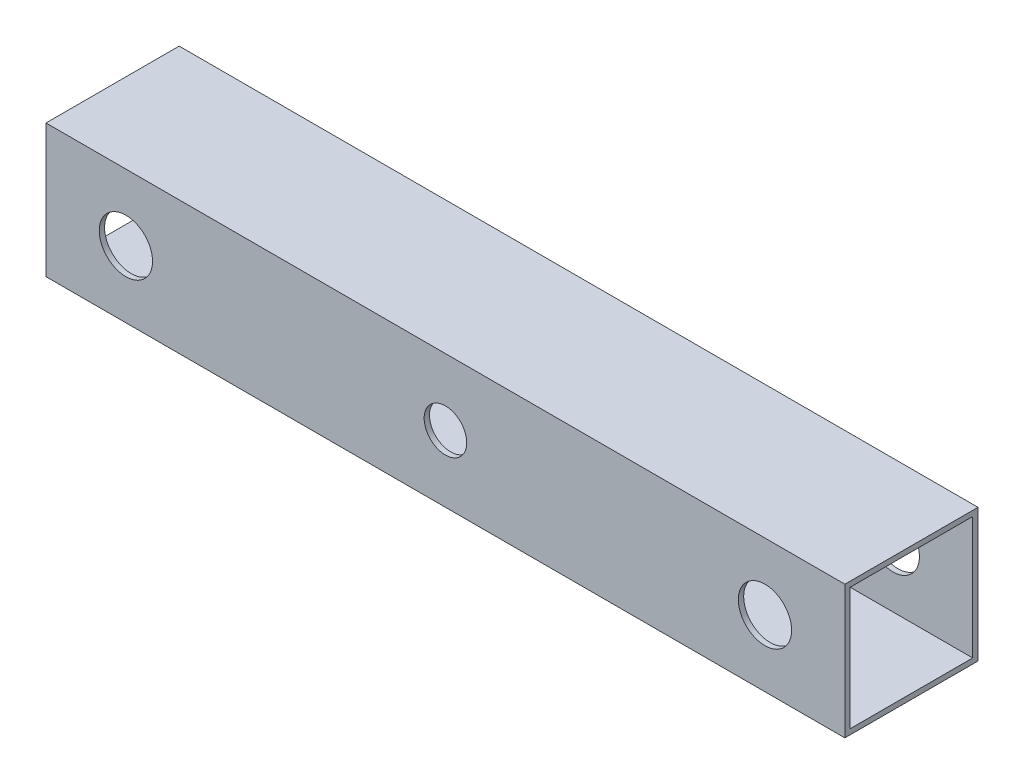
SolidWorks part; units mm, degrees
ref_plane "Front Plane" through (0, 0, 0) normal (0, 0, 1) x (1, 0, 0)
ref_plane "Top Plane" through (0, 0, 0) normal (0, 1, 0) x (1, 0, 0)
ref_plane "Right Plane" through (0, 0, 0) normal (1, 0, 0) x (0, 0, -1)
sketch "Sketch1" plane through (0, 0, 0) normal (1, 0, 0) x (0, 0, -1)
  line L0 (-12.5, 12.5) -> (12.5, 12.5)
  line L2 (-11.5, -11.5) -> (-11.5, 11.5)
  line L3 (-11.5, 11.5) -> (11.5, 11.5)
  line L5 (-11.5, -11.5) -> (11.5, 11.5) construction
  line L6 (-11.5, 11.5) -> (11.5, -11.5) construction
  line L7 (12.5, -12.5) -> (12.5, 12.5)
  line L8 (-12.5, -12.5) -> (12.5, -12.5)
  line L9 (-12.5, -12.5) -> (-12.5, 12.5)
  line L12 (-11.5, 11.5) -> (11.5, 11.5) construction
  line L13 (-11.5, -11.5) -> (11.5, -11.5)
  line L14 (-11.5, -11.5) -> (-11.5, 11.5) construction
  line L15 (11.5, -11.5) -> (11.5, 11.5)
  line L16 (-11.5, -11.5) -> (11.5, -11.5) construction
  line L18 (11.5, -11.5) -> (11.5, 11.5) construction
  point P0 (0, 0)
  dimension "D2" = 25
  dimension "D1" = 1
extrude "Boss-Extrude1" add sketch "Sketch1" along normal blind 150
sketch "Sketch2" plane through (0, 0, 12.5) normal (0, 0, 1) x (1, 0, 0)
  line L0 (0, 0) -> (150, 0) construction
  line L1 (150, 12.5) -> (150, -12.5) construction
  circle A0 centre (75, 0) radius 4
  circle A1 centre (15, 0) radius 5
  circle A2 centre (135, 0) radius 5
  dimension "D1" = 8
  dimension "D2" = 10
  dimension "D3" = 60
  dimension "D4" = 60
extrude "Cut-Extrude1" cut sketch "Sketch2" against normal through all
